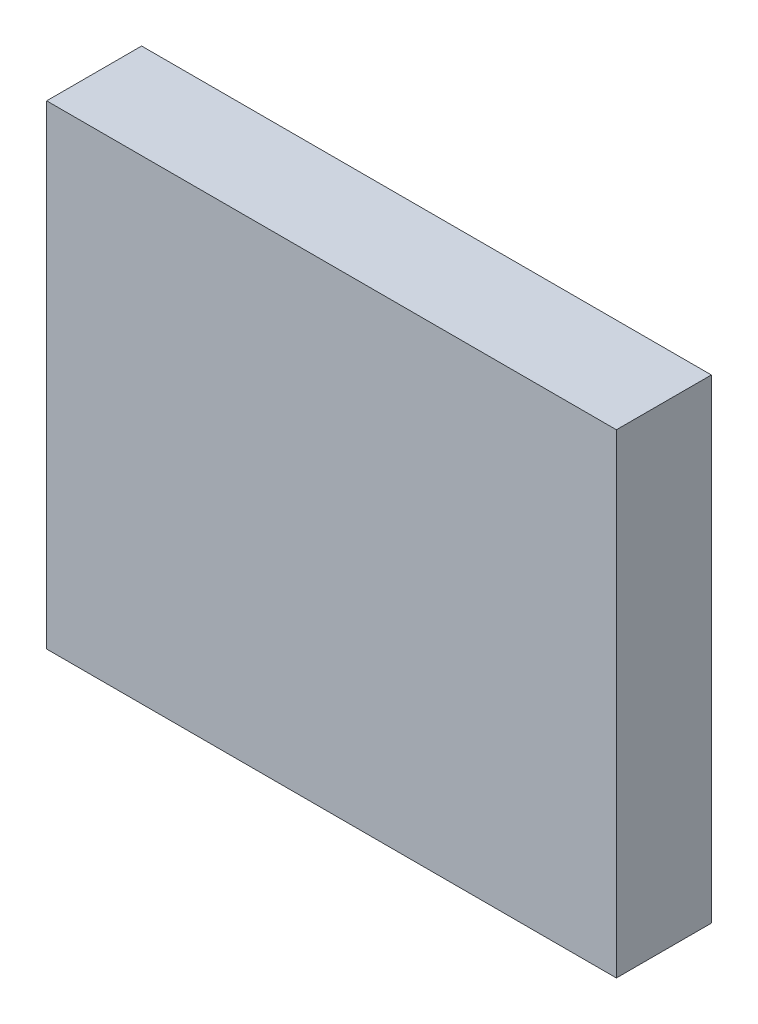
SolidWorks part; units mm, degrees
ref_plane "Alzado" through (0, 0, 0) normal (0, 0, 1) x (1, 0, 0)
ref_plane "Planta" through (0, 0, 0) normal (0, 1, 0) x (1, 0, 0)
ref_plane "Vista lateral" through (0, 0, 0) normal (1, 0, 0) x (0, 0, -1)
sketch "Croquis1" plane through (0, 0, 0) normal (0, 0, 1) x (1, 0, 0)
  line L1 (30, -25) -> (-30, -25)
  line L2 (30, -25) -> (30, 25)
  line L3 (30, 25) -> (-30, 25)
  line L4 (-30, -25) -> (-30, 25)
  line L5 (30, -25) -> (-30, 25) construction
  line L6 (30, 25) -> (-30, -25) construction
  point P0 (0, 0)
  dimension "D1" = 60
  dimension "D2" = 50
extrude "Saliente-Extruir1" add sketch "Croquis1" along normal blind 10
